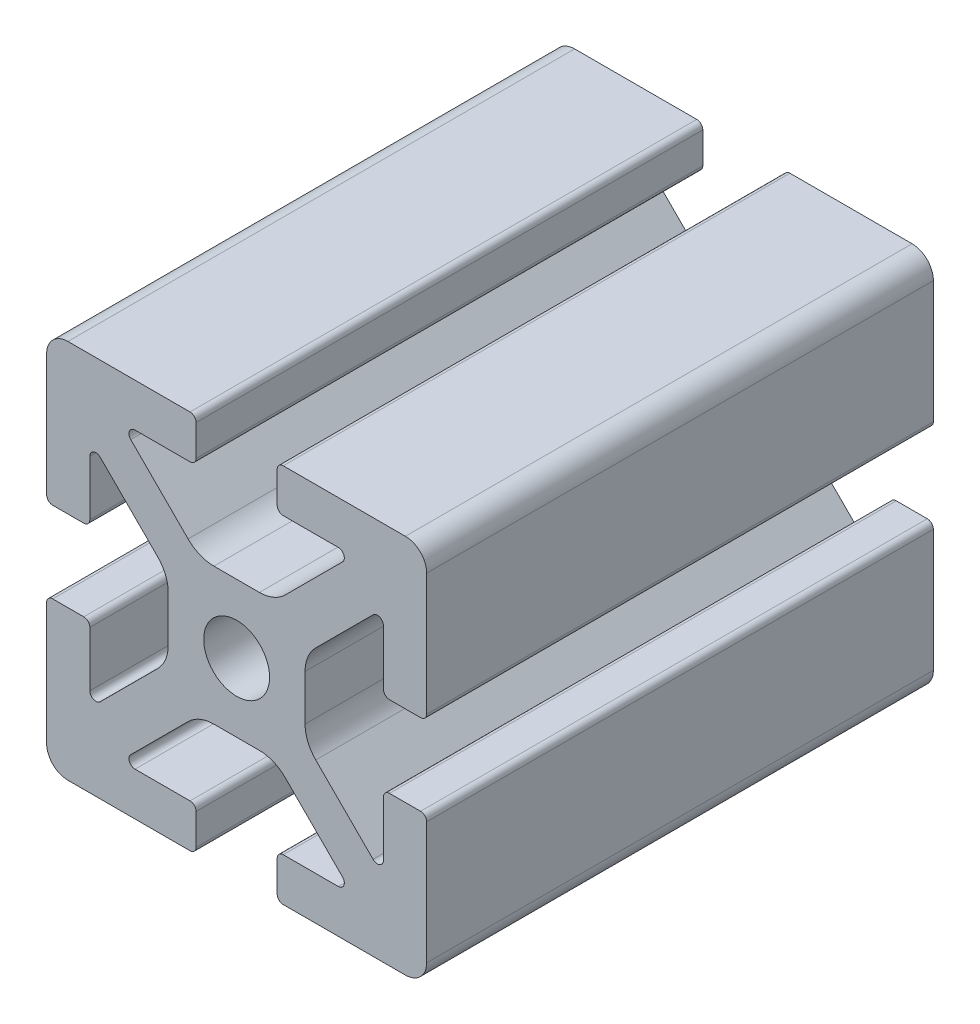
SolidWorks part; units mm, degrees
ref_plane "Front Plane" through (0, 0, 0) normal (0, 0, 1) x (1, 0, 0)
ref_plane "Top Plane" through (0, 0, 0) normal (0, 1, 0) x (1, 0, 0)
ref_plane "Right Plane" through (0, 0, 0) normal (1, 0, 0) x (0, 0, -1)
sketch "Sketch2" plane through (0, 0, 0) normal (0, 0, 1) x (1, 0, 0)
  line L0 (0, 19.05) -> (0, -19.05) construction
  line L1 (-19.05, 0) -> (19.05, 0) construction
  line L2 (4.064, -19.05) -> (19.05, -19.05)
  line L3 (19.05, -19.05) -> (19.05, -4.064)
  line L4 (4.064, -19.05) -> (4.064, -14.7193)
  line L5 (4.064, -14.7193) -> (11.6571, -14.7193)
  line L6 (11.6571, -14.7193) -> (3.7958, -6.858)
  line L7 (0, 0) -> (19.05, -19.05) construction
  line L8 (19.05, -4.064) -> (14.7193, -4.064)
  line L9 (14.7193, -4.064) -> (14.7193, -11.6571)
  line L10 (14.7193, -11.6571) -> (6.858, -3.7958)
  line L11 (10.7887, -7.7264) -> (7.7264, -10.7887) construction
  circle A0 centre (0, 0) radius 3.302
  arc A1 (10.1854, -14.7193) -> (10.6165, -13.6787) centre (10.1854, -14.1097) ccw construction
  point P8 (0, -6.858)
  point P16 (9.2576, -9.2576)
  dimension "Center Hole Diameter" = 6.604
  dimension "D3" = 0.6096
  dimension "Rail Height" = 38.1
  dimension "Rail Width" = 38.1
  dimension "T-Slot Width" = 8.128
  dimension "Slot Depth" = 12.192
  dimension "Slot Inner Width" = 21.59
sketch "Sketch3" plane through (0, 0, 0) normal (1, 0, 0) x (0, 0, -1)
  line L0 (-25.4, -19.05) -> (25.4, -19.05) construction
  dimension "Length" = 50.8
sketch "Sketch4" plane through (0, 0, 0) normal (0, 0, 1) x (1, 0, 0)
  line L0 (4.6736, -19.05) -> (16.9164, -19.05)
  line L1 (4.064, -19.05) -> (19.05, -19.05) construction
  line L2 (4.064, -19.05) -> (4.064, -14.7193) construction
  line L3 (4.064, -14.7193) -> (11.6571, -14.7193) construction
  line L4 (4.064, -15.3289) -> (4.064, -18.4404)
  line L5 (4.6736, -14.7193) -> (10.1854, -14.7193)
  line L6 (0, -6.858) -> (2.2807, -6.858)
  line L7 (11.6571, -14.7193) -> (3.7958, -6.858) construction
  line L8 (4.867, -7.9293) -> (10.6165, -13.6787)
  line L9 (19.05, -19.05) -> (19.05, -4.064) construction
  line L10 (14.7193, -11.6571) -> (6.858, -3.7958) construction
  line L11 (14.7193, -4.064) -> (14.7193, -11.6571) construction
  line L12 (14.7193, -10.1854) -> (14.7193, -4.6736)
  line L13 (19.05, -4.064) -> (14.7193, -4.064) construction
  line L14 (15.3289, -4.064) -> (18.4404, -4.064)
  line L15 (19.05, -4.6736) -> (19.05, -16.9164)
  line L16 (13.6787, -10.6165) -> (7.9293, -4.867)
  line L17 (6.858, 0) -> (6.858, -2.2807)
  line L18 (-19.05, 0) -> (19.05, 0) construction
  line L19 (0, -6.858) -> (0, -3.302)
  line L20 (0, 19.05) -> (0, -19.05) construction
  line L21 (6.858, 0) -> (3.302, 0)
  arc A0 (4.064, -18.4404) -> (4.6736, -19.05) centre (4.6736, -18.4404) ccw
  arc A1 (10.1854, -14.7193) -> (10.6165, -13.6787) centre (10.1854, -14.1097) ccw construction
  arc A2 (4.064, -15.3289) -> (4.6736, -14.7193) centre (4.6736, -15.3289) cw
  arc A3 (10.1854, -14.7193) -> (10.6165, -13.6787) centre (10.1854, -14.1097) ccw
  arc A4 (2.2807, -6.858) -> (4.867, -7.9293) centre (2.2807, -10.5156) cw
  arc A5 (16.9164, -19.05) -> (19.05, -16.9164) centre (16.9164, -16.9164) ccw
  arc A6 (13.6787, -10.6165) -> (14.7193, -10.1854) centre (14.1097, -10.1854) ccw
  arc A7 (14.7193, -4.6736) -> (15.3289, -4.064) centre (15.3289, -4.6736) cw
  arc A8 (18.4404, -4.064) -> (19.05, -4.6736) centre (18.4404, -4.6736) cw
  arc A9 (7.9293, -4.867) -> (6.858, -2.2807) centre (10.5156, -2.2807) cw
  circle A10 centre (0, 0) radius 3.302 construction
  arc A11 (0, -3.302) -> (3.302, 0) centre (0, 0) ccw
  dimension "D1" = 2.1336
  dimension "D2" = 3.6576
extrude "Boss-Extrude1" add sketch "Sketch4" along normal mid plane 50.8
mirror "Mirror1" about plane through (0, 0, 0) normal (1, 0, 0) of bodies 134
mirror "Mirror2" about plane through (0, 0, 0) normal (0, 1, 0) of bodies 135
equation "\"D3@Sketch2\"=\"T-Slot Width@Sketch2\"*0.075"
equation "\"D1@Sketch4\"=\"D3@Sketch2\"*3.5"
equation "\"D2@Sketch4\"=\"D3@Sketch2\"*6"
equation "\"D1@Boss-Extrude1\"=\"Length@Sketch3\""
